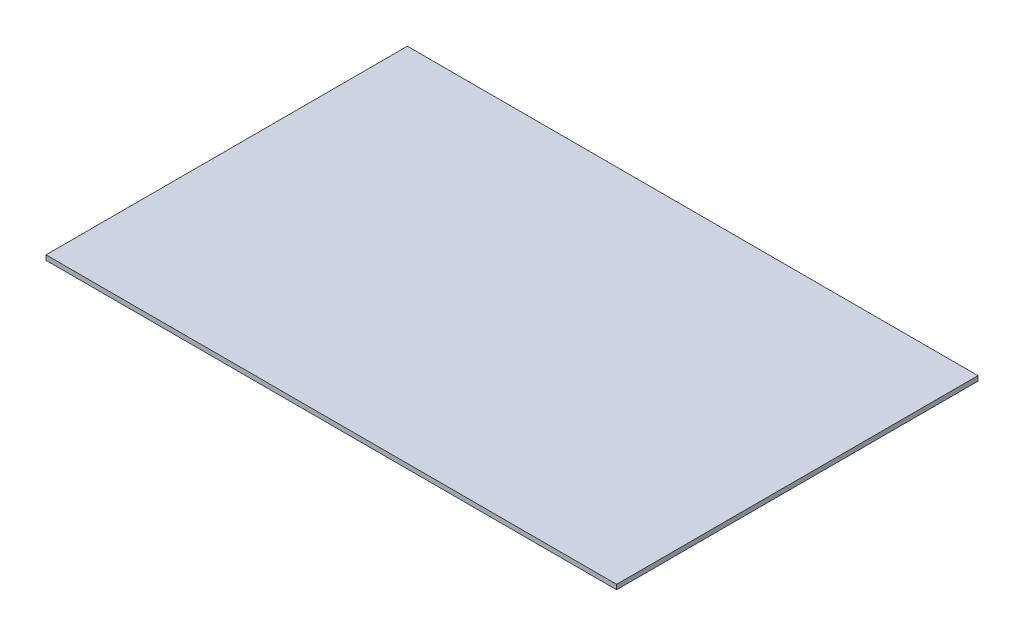
SolidWorks part; units mm, degrees
material "6061-T6 (SS)"
ref_plane "Front Plane" through (0, 0, 0) normal (0, 0, 1) x (1, 0, 0)
ref_plane "Top Plane" through (0, 0, 0) normal (0, 1, 0) x (1, 0, 0)
ref_plane "Right Plane" through (0, 0, 0) normal (1, 0, 0) x (0, 0, -1)
sketch "Sketch1" plane through (0, 0, 0) normal (0, 1, 0) x (1, 0, 0)
  line L1 (-120, 76) -> (120, 76)
  line L2 (-120, 76) -> (-120, -76)
  line L3 (-120, -76) -> (120, -76)
  line L4 (120, 76) -> (120, -76)
  line L5 (-120, 76) -> (120, -76) construction
  line L6 (-120, -76) -> (120, 76) construction
  point P0 (0, 0)
  dimension "D1" = 240
  dimension "D2" = 152
extrude "Boss-Extrude1" add sketch "Sketch1" along normal blind 2
